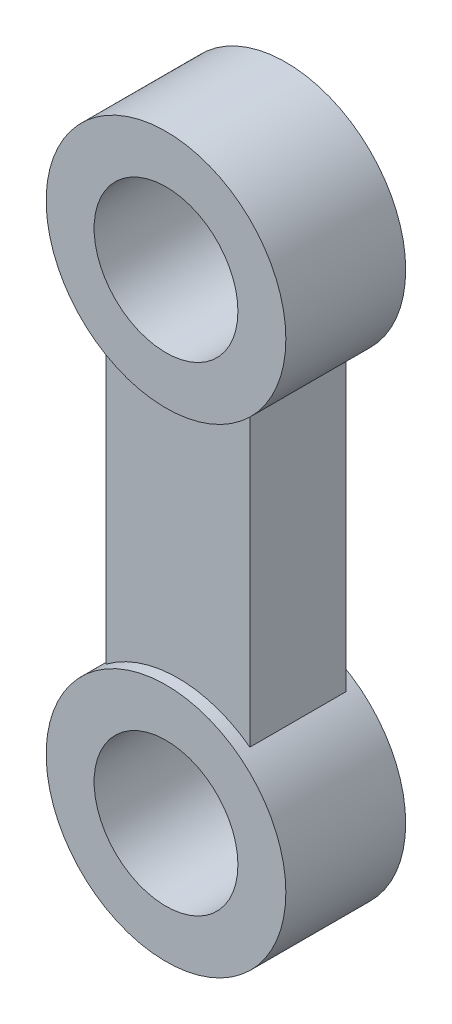
SolidWorks part; units mm, degrees
ref_plane "Front Plane" through (0, 0, 0) normal (0, 0, 1) x (1, 0, 0)
ref_plane "Top Plane" through (0, 0, 0) normal (0, 1, 0) x (1, 0, 0)
ref_plane "Right Plane" through (0, 0, 0) normal (1, 0, 0) x (0, 0, -1)
sketch "Sketch1" plane through (0, 0, 0) normal (0, 0, 1) x (1, 0, 0)
  circle A0 centre (0, 0) radius 25
  circle A1 centre (0, 0) radius 15
  dimension "D1" = 50
  dimension "D2" = 30
extrude "Boss-Extrude1" add sketch "Sketch1" along normal mid plane 25
sketch "Sketch2" plane through (0, 0, 0) normal (0, 1, 0) x (1, 0, 0)
  line L1 (15, -10) -> (-15, -10)
  line L2 (15, -10) -> (15, 10)
  line L3 (15, 10) -> (-15, 10)
  line L4 (-15, -10) -> (-15, 10)
  line L5 (15, -10) -> (-15, 10) construction
  line L6 (15, 10) -> (-15, -10) construction
  point P0 (0, 0)
  dimension "D1" = 20
  dimension "D2" = 30
extrude "Boss-Extrude2" add sketch "Sketch2" against normal blind 100
sketch "Sketch3" plane through (0, 0, 0) normal (0, 0, 1) x (1, 0, 0)
  line L0 (-15, -100) -> (15, -100) construction
  circle A0 centre (0, -100) radius 25
  circle A1 centre (0, -100) radius 15
  dimension "D1" = 30
  dimension "D2" = 50
extrude "Boss-Extrude3" add sketch "Sketch3" along normal mid plane 25
sketch "Sketch4" plane through (0, 0, 0) normal (0, 0, 1) x (1, 0, 0)
  line L0 (-15, -100) -> (15, -100) construction
  circle A0 centre (0, 0) radius 15
  circle A1 centre (0, -100) radius 15
extrude "Cut-Extrude1" cut sketch "Sketch4" along normal through all both and the other way through all
